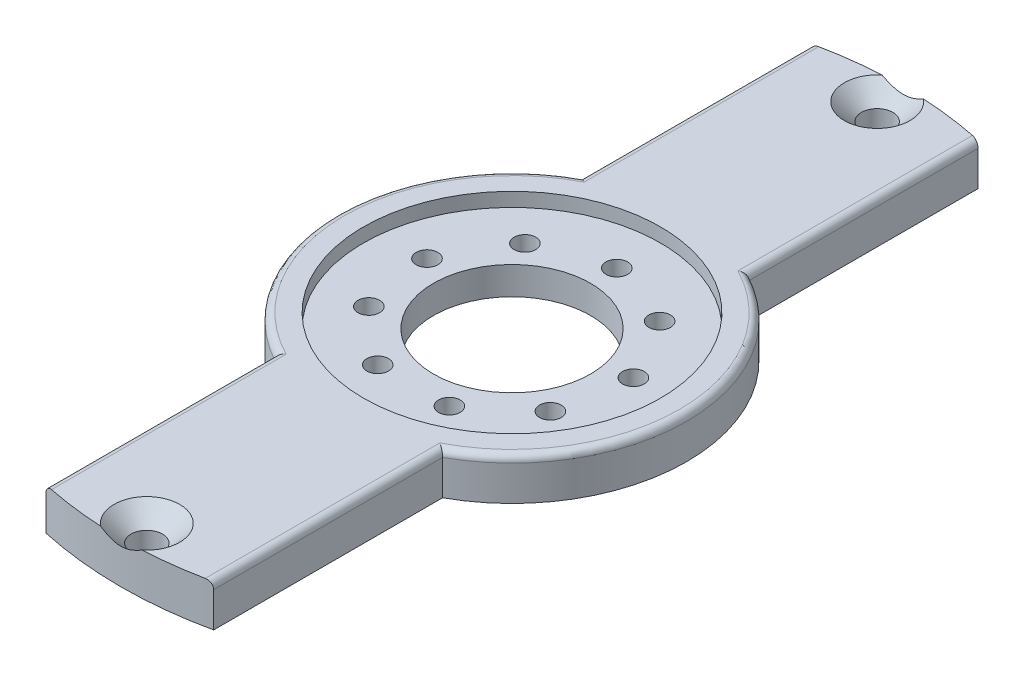
SolidWorks part; units mm, degrees
ref_plane "Front Plane" through (0, 0, 0) normal (0, 0, 1) x (1, 0, 0)
ref_plane "Top Plane" through (0, 0, 0) normal (0, 1, 0) x (1, 0, 0)
ref_plane "Right Plane" through (0, 0, 0) normal (1, 0, 0) x (0, 0, -1)
sketch "Sketch2" plane through (0, 0, 0) normal (0, 1, 0) x (1, 0, 0)
  line L1 (0, 0) -> (0, 56)
  line L2 (0, 0) -> (0, -56)
  line L3 (-12, -54.6992) -> (-12, -21.9317)
  line L4 (12, -54.6992) -> (12, -21.9317)
  line L5 (0, 50) -> (0, 56)
  line L6 (12, 48.5386) -> (-12, 48.5386)
  line L7 (0, 48.5386) -> (0, 56)
  line L8 (0, 56) -> (0, 48.5386)
  line L9 (-12, -48.5386) -> (12, -48.5386)
  line L10 (12, 21.9317) -> (12, 54.6992)
  line L11 (-12, 21.9317) -> (-12, 54.6992)
  arc A0 (-12, -54.6992) -> (12, -54.6992) centre (0, 0) ccw
  circle A1 centre (0, 0) radius 25
  circle A2 centre (0, 0) radius 21.25
  arc A3 (12, 54.6992) -> (-12, 54.6992) centre (0, 0) ccw
  arc A4 (-12, -48.5386) -> (12, -48.5386) centre (0, 0) ccw
  circle A6 centre (0, 52.2693) radius 2
  circle A7 centre (0, -52.2693) radius 2
  arc A8 (12, 48.5386) -> (-12, 48.5386) centre (0, 0) ccw
  point P8 (0, 0)
  dimension "D1" = 112
  dimension "D2" = 42.5
  dimension "D3" = 50
  dimension "D5" = 100
  dimension "D6" = 4
  dimension "D7" = 4
  dimension "D4" = 24
extrude "Boss-Extrude2" add sketch "Sketch2" along normal blind 6 contours L2 A7 A4 L3 A0 | A7 L2 | A7 L2 | L2 A7 A0 L4 A4 | L9 A4 L2 | A1 L3 L9 L2 | A1 L2 L9 L4 | L2 A4 L9 | A8 L1 A6 A3 L11 | L8 A6 | L8 A6 | A8 L10 A3 L1 A6 | L1 A8 L6 | L6 A8 L1 | A1 L1 L6 L11 | A1 L10 L6 L1 | A2 L1 A1 L2 | L1 A2 L2 | L2 A2 L1 | A2 L2 A1 L1
sketch "Sketch5" plane through (0, 6, 0) normal (0, 1, 0) x (1, 0, 0)
  line L0 (-12, 54.6992) -> (-12, 48.5386)
  line L1 (-12, 21.9317) -> (-12, 54.6992) construction
  line L2 (-12, 48.5386) -> (12, 48.5386)
  line L3 (12, 21.9317) -> (12, 54.6992) construction
  line L4 (0, 56) -> (0, 48.5386)
  arc A0 (12, 54.6992) -> (-12, 54.6992) centre (0, 0) ccw construction
  point P15 (0, 52.2693)
  dimension "D1" = 6.1605
hole_wizard "CSK for M4 Flat Head Machine Screw1" positions "Sketch5" profile "Sketch6" countersink size "M4" standard "ANSI Metric" end condition through all
sketch "Sketch6" plane through (0, 6, -52.2693) normal (1, 0, 0) x (0, 0, 1)
  line L0 (0, 0) -> (0, 6)
  line L1 (0, 6) -> (2.25, 6)
  line L2 (2.25, 6) -> (2.25, 2.45)
  line L3 (2.25, 2.45) -> (4.7, 0)
  line L5 (4.7, 0) -> (0, 0)
  line L6 (-2.25, 2.45) -> (-4.7, 0) construction
  line L11 (0, -6.35) -> (0, 107.95) construction
  dimension "Thru Hole Dia." = 4.5
  dimension "Thru Hole Depth" = 6
  dimension "Near C'Sink Dia." = 9.4
  dimension "Near C'Sink Angle" = 90
mirror "Mirror1" about plane through (0, 0, 0) normal (0, 0, 1) of "CSK for M4 Flat Head Machine Screw1"
sketch "Sketch7" plane through (0, 6, 0) normal (0, 1, 0) x (1, 0, 0)
  circle A0 centre (0, 0) radius 21.25
  dimension "D1" = 42.5
extrude "Cut-Extrude2" cut sketch "Sketch7" against normal blind 2
sketch "Sketch8" plane through (0, 4, 0) normal (0, 1, 0) x (1, 0, 0)
  circle A0 centre (0, 0) radius 11.25
  dimension "D1" = 22.5
extrude "Cut-Extrude3" cut sketch "Sketch8" against normal through all
sketch "Sketch9" plane through (0, 4, 0) normal (0, 1, 0) x (1, 0, 0)
  circle A0 centre (0, 0) radius 15
  circle A1 centre (0, 15) radius 1.55
  circle A2 centre (9.6418, 11.4907) radius 1.55
  circle A3 centre (14.7721, 2.6047) radius 1.55
  circle A4 centre (12.9904, -7.5) radius 1.55
  circle A5 centre (5.1303, -14.0954) radius 1.55
  circle A6 centre (-5.1303, -14.0954) radius 1.55
  circle A7 centre (-12.9904, -7.5) radius 1.55
  circle A8 centre (-14.7721, 2.6047) radius 1.55
  circle A9 centre (-9.6418, 11.4907) radius 1.55
  point P24 (0, 0)
  dimension "D1" = 9
  dimension "D2" = 3.1
extrude "Cut-Extrude4" cut sketch "Sketch9" against normal through all contours A0 A1 | A0 A1 | A0 A2 | A0 A2 | A0 A3 | A0 A3 | A0 A4 | A0 A4 | A0 A5 | A0 A5 | A0 A6 | A0 A6 | A0 A7 | A0 A7 | A0 A8 | A0 A8 | A0 A9 | A0 A9
fillet "Fillet1" radius 1 6 edges at (12, 6, 38.3154) (-12, 6, 38.3154) (-25, 6, 0) (-12, 6, -38.3154) (25, 6, 0) (12, 6, -38.3154)
